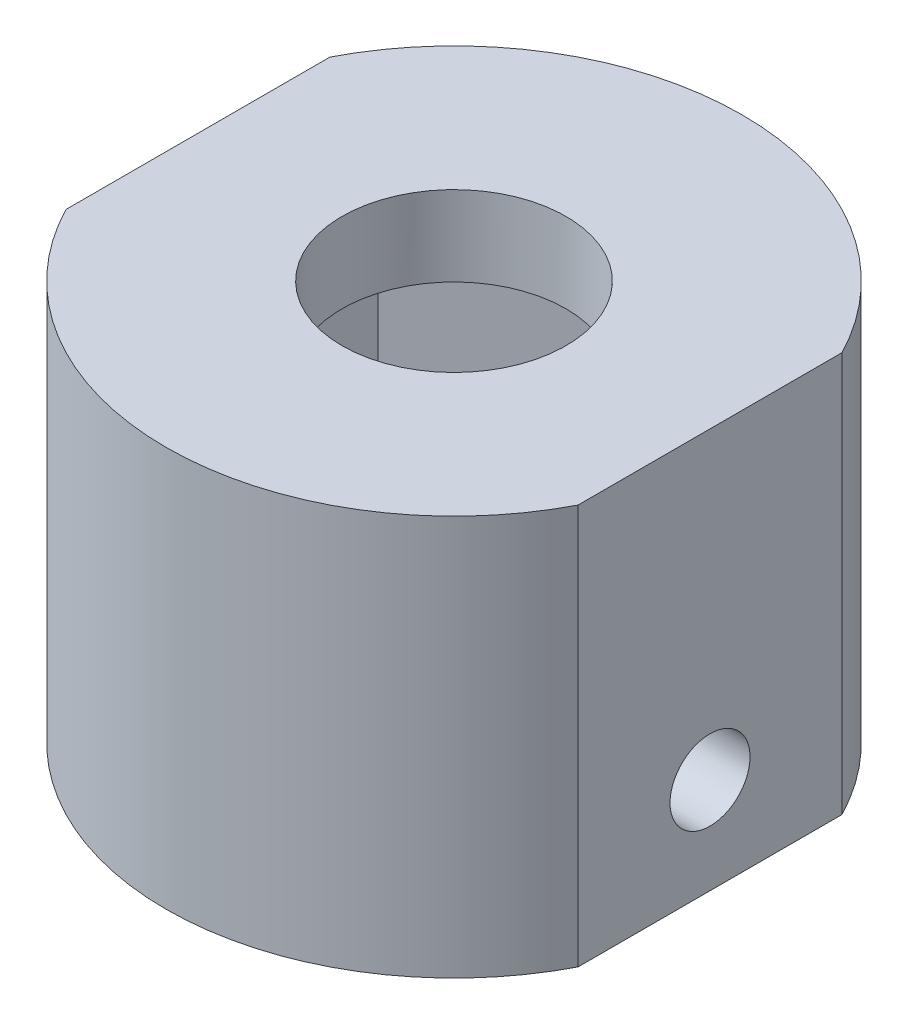
SolidWorks part; units mm, degrees
ref_plane "Plano frontal" through (0, 0, 0) normal (0, 0, 1) x (1, 0, 0)
ref_plane "Plano superior" through (0, 0, 0) normal (0, 1, 0) x (1, 0, 0)
ref_plane "Plano direito" through (0, 0, 0) normal (1, 0, 0) x (0, 0, -1)
sketch "Esboço9" plane through (0, 0, 0) normal (0, 1, 0) x (1, 0, 0)
  circle A0 centre (0, 0) radius 9
  dimension "D1" = 18
extrude "Ressalto-extrusão1" add sketch "Esboço9" along normal blind 12.5
sketch "Esboço12" plane through (0, 12.5, 0) normal (0, 1, 0) x (1, 0, 0)
  circle A0 centre (0, 0) radius 3.5
  dimension "D1" = 7
extrude "Corte-extrusão9" cut sketch "Esboço12" against normal through all
sketch "Esboço13" plane through (0, 0, 0) normal (0, -1, 0) x (1, 0, 0)
  line L1 (0, 6.4952) -> (-5.625, 3.2476)
  line L2 (-5.625, 3.2476) -> (-5.625, -3.2476)
  line L3 (-5.625, -3.2476) -> (0, -6.4952)
  line L4 (0, -6.4952) -> (5.625, -3.2476)
  line L5 (5.625, -3.2476) -> (5.625, 3.2476)
  line L6 (5.625, 3.2476) -> (0, 6.4952)
  circle A0 centre (0, 0) radius 5.625 construction
  dimension "D1" = 11.25
extrude "Corte-extrusão10" cut sketch "Esboço13" against normal blind 10
sketch "Esboço14" plane through (0, 0, 0) normal (1, 0, 0) x (0, 0, -1)
  circle A0 centre (0, 3) radius 1.25
  dimension "D1" = 2.5
  dimension "D2" = 3
extrude "Corte-extrusão11" cut sketch "Esboço14" against normal through all both and the other way through all
sketch "Esboço15" plane through (0, 0, 0) normal (0, -1, 0) x (1, 0, 0)
  line L0 (-8, 4.1231) -> (-8, -4.1231)
  line L1 (8, 4.1231) -> (8, -4.1231)
  arc A0 (-8, 4.1231) -> (-8, -4.1231) centre (0, 0) ccw
  arc A1 (8, -4.1231) -> (8, 4.1231) centre (0, 0) ccw
  dimension "D1" = 8
  dimension "D2" = 8
extrude "Corte-extrusão12" cut sketch "Esboço15" against normal through all
